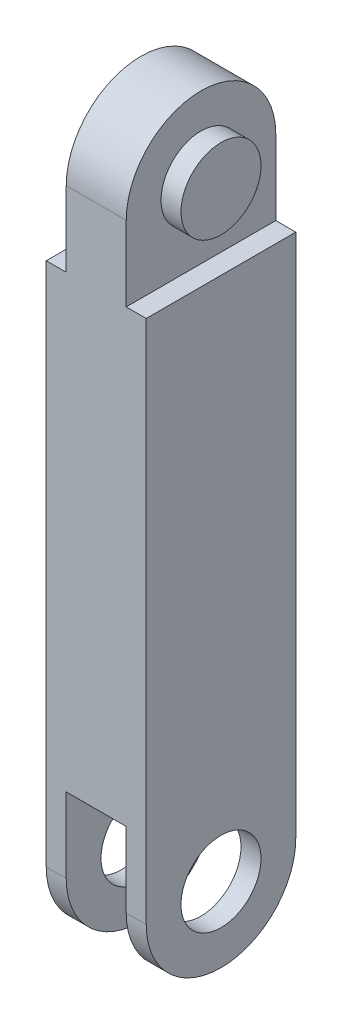
SolidWorks part; units mm, degrees
ref_plane "Front Plane" through (0, 0, 0) normal (0, 0, 1) x (1, 0, 0)
ref_plane "Top Plane" through (0, 0, 0) normal (0, 1, 0) x (1, 0, 0)
ref_plane "Right Plane" through (0, 0, 0) normal (1, 0, 0) x (0, 0, -1)
sketch "Sketch1" plane through (0, 0, 0) normal (1, 0, 0) x (0, 0, -1)
  line L0 (-74.7678, 0) -> (-74.7678, 600)
  line L1 (74.7678, 0) -> (74.7678, 600)
  arc A0 (-74.7678, 600) -> (74.7678, 600) centre (0, 600) cw
  arc A1 (-74.7678, 0) -> (74.7678, 0) centre (0, 0) ccw
extrude "Boss-Extrude1" add sketch "Sketch1" along normal blind 100 contours L0 A0 L1 A1
sketch "Sketch7" plane through (100, 0, 0) normal (1, 0, 0) x (0, 0, -1)
  line L0 (74.7678, 0) -> (74.7678, 600) construction
  line L1 (-74.7678, 600) -> (-74.7678, 525)
  line L2 (-74.7678, 0) -> (-74.7678, 600) construction
  line L3 (74.7678, 600) -> (74.7678, 525)
  line L4 (74.7678, 525) -> (-74.7678, 525)
  arc A0 (-74.7678, 600) -> (74.7678, 600) centre (0, 600) cw
  dimension "D1" = 75
sketch "Sketch8" plane through (0, 0, 0) normal (-1, 0, 0) x (0, 0, 1)
  line L0 (74.7678, 0) -> (74.7678, 600) construction
  line L1 (-74.7678, 600) -> (-74.7678, 525)
  line L2 (-74.7678, 0) -> (-74.7678, 600) construction
  line L3 (74.7678, 600) -> (74.7678, 525)
  line L4 (74.7678, 525) -> (-74.7678, 525)
  arc A0 (-74.7678, 600) -> (74.7678, 600) centre (0, 600) cw
  dimension "D1" = 75
  dimension "D2" = 75
extrude "Cut-Extrude2" cut sketch "Sketch8" against normal blind 20
extrude "Cut-Extrude3" cut sketch "Sketch7" against normal blind 20 contours L4 L1 A0 L3
sketch "Sketch10" plane through (80, 0, 0) normal (1, 0, 0) x (0, 0, -1)
  circle A0 centre (0, 600) radius 40
sketch "Sketch11" plane through (20, 0, 0) normal (-1, 0, 0) x (0, 0, 1)
  circle A0 centre (0, 600) radius 40
extrude "Boss-Extrude6" add sketch "Sketch10" along normal blind 20 contours A0
extrude "Boss-Extrude7" add sketch "Sketch11" along normal blind 20 contours A0
sketch "Sketch16" plane through (0, 0, 74.7678) normal (0, 0, 1) x (1, 0, 0)
  line L4 (80, -75) -> (20, -75)
  line L5 (80, -75) -> (80, 75)
  line L6 (80, 75) -> (20, 75)
  line L7 (20, -75) -> (20, 75)
  line L8 (80, -75) -> (20, 75) construction
  line L9 (80, 75) -> (20, -75) construction
sketch "Sketch19" plane through (0, 0, 0) normal (-1, 0, 0) x (0, 0, 1)
  circle A0 centre (0, 0) radius 40
extrude "Cut-Extrude7" cut sketch "Sketch19" against normal blind 285
extrude "Cut-Extrude8" cut sketch "Sketch16" against normal blind 285 contours L6 L7 L4 L5
